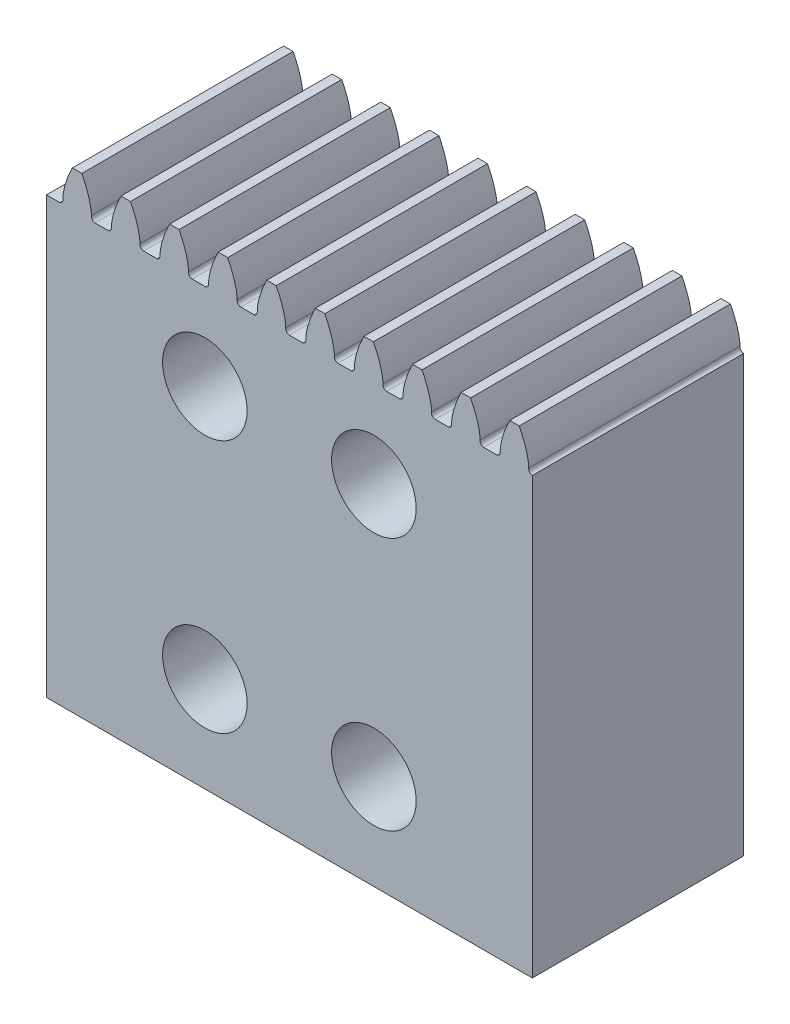
SolidWorks part; units mm, degrees
material "ABS"
ref_plane "Płaszczyzna przednia" through (0, 0, 0) normal (0, 0, 1) x (1, 0, 0)
ref_plane "Płaszczyzna górna" through (0, 0, 0) normal (0, 1, 0) x (1, 0, 0)
ref_plane "Płaszczyzna prawa" through (0, 0, 0) normal (1, 0, 0) x (0, 0, -1)
sketch "Szkic1" plane through (0, 0, 0) normal (0, 0, 1) x (1, 0, 0)
  line L1 (-11.5, -8.5) -> (11.5, -8.5)
  line L2 (-11.5, -8.5) -> (-11.5, 8.5)
  line L3 (-11.5, 8.5) -> (11.5, 8.5)
  line L4 (11.5, -8.5) -> (11.5, 8.5)
  line L5 (-11.5, -8.5) -> (11.5, 8.5) construction
  line L6 (-11.5, 8.5) -> (11.5, -8.5) construction
  line L7 (-11.5, 8.5) -> (11.5, 8.5)
  line L8 (-11.5, 8.5) -> (-11.5, 10.1)
  line L9 (-11.5, 10.1) -> (11.5, 10.1)
  line L10 (11.5, 8.5) -> (11.5, 10.1)
  point P0 (0, 0)
  dimension "D1" = 17
  dimension "D2" = 23
  dimension "D3" = 1.6
  dimension "D4" = 23
extrude "Dodanie-wyciągnięcie1" add sketch "Szkic1" along normal blind 10 contours L1 L4 L3 L2 | L3 L10 L9 L8
sketch "Szkic2" plane through (0, 0, 10) normal (0, 0, 1) x (1, 0, 0)
  line L0 (0, 0) -> (-8.8665, 0) construction
  line L2 (0, 0) -> (0, 7.3642) construction
  circle A0 centre (-4, 6) radius 1.25
  circle A1 centre (4, 6) radius 1.25
  circle A2 centre (-4, -6) radius 1.25
  circle A3 centre (4, -6) radius 1.25
  point P12 (0, 0)
  point P13 (0, 0)
  point P14 (0, 0)
  dimension "D1" = 2.5
  dimension "D2" = 8
  dimension "D3" = 12
extrude "Wytnij-wyciągnięcie1" cut sketch "Szkic2" against normal blind 10
sketch "Szkic3" plane through (0, 0, 10) normal (0, 0, 1) x (1, 0, 0)
  circle A0 centre (-4, 6) radius 2
  circle A1 centre (4, 6) radius 2
  circle A2 centre (4, -6) radius 2
  circle A3 centre (-4, -6) radius 2
  dimension "D1" = 4
extrude "Wytnij-wyciągnięcie2" cut sketch "Szkic3" against normal blind 7
sketch "Szkic4" plane through (0, 0, 10) normal (0, 0, 1) x (1, 0, 0)
  line L0 (11.3269, 10.2979) -> (11.3285, 10.3258)
  line L1 (9.9801, 10.3241) -> (9.9818, 10.2962)
  line L2 (9.8093, 10.0979) -> (11.5, 10.1)
  line L4 (-11.5, 10.1) -> (11.5, 10.1) construction
  line L5 (-11.5, 10.1) -> (11.5, 10.1)
  arc A1 (11.3269, 10.2979) -> (11.5, 10.1) centre (11.5141, 10.287) ccw
  arc A2 (10.878, 11.8171) -> (10.427, 11.8165) centre (10.6685, -0.9312) ccw
  arc A3 (9.8093, 10.0979) -> (9.9818, 10.2962) centre (9.7947, 10.2848) ccw
  spline S0 degree 4 poles (11.3285, 10.3258) (11.3289, 10.3341) (11.3292, 10.3575) (11.3276, 10.4017) (11.3221, 10.4738) (11.3105, 10.5653) (11.2904, 10.6831) (11.2601, 10.8209) (11.2201, 10.9711) (11.1691, 11.1329) (11.1119, 11.2927) (11.049, 11.4504) (10.9829, 11.6013) (10.9305, 11.712) (10.8949, 11.7836) (10.878, 11.8171) knots 0 0 0 0 0 0.005377 0.015084 0.028532 0.04661 0.064855 0.092111 0.119476 0.146842 0.174209 0.201575 0.228941 0.253142 0.253142 0.253142 0.253142 0.253142
  spline S1 degree 4 poles (10.427, 11.8165) (10.4101, 11.783) (10.3747, 11.7113) (10.3225, 11.6005) (10.2569, 11.4494) (10.1943, 11.2915) (10.1375, 11.1316) (10.087, 10.9696) (10.0473, 10.8193) (10.0174, 10.6815) (9.9976, 10.5637) (9.9862, 10.4721) (9.9808, 10.4) (9.9794, 10.3558) (9.9798, 10.3324) (9.9801, 10.3241) knots 0 0 0 0 0 0.024201 0.051567 0.078933 0.1063 0.133666 0.161032 0.188287 0.206532 0.22461 0.238059 0.247765 0.253142 0.253142 0.253142 0.253142 0.253142
extrude "Dodanie-wyciągnięcie2" add sketch "Szkic4" against normal blind 10
pattern_linear "Szyk liniowy1" count 10 spacing 2.3 along (1, 0, 0) of "Dodanie-wyciągnięcie2"
sketch "Szkic5" plane through (0, -8.5, 0) normal (0, -1, 0) x (1, 0, 0)
  line L4 (-11.5, 0) -> (11.5, 0)
  line L5 (11.5, 0) -> (11.5, 10)
  line L6 (11.5, 10) -> (-11.5, 10)
  line L7 (-11.5, 10) -> (-11.5, 0)
  line L8 (-11.5, 0) -> (11.5, 0)
  line L9 (11.5, 0) -> (11.5, 10)
  line L10 (11.5, 10) -> (-11.5, 10)
  line L11 (-11.5, 10) -> (-11.5, 0)
  dimension "D1" = 0
extrude "Dodanie-wyciągnięcie3" add sketch "Szkic5" along normal blind 2
